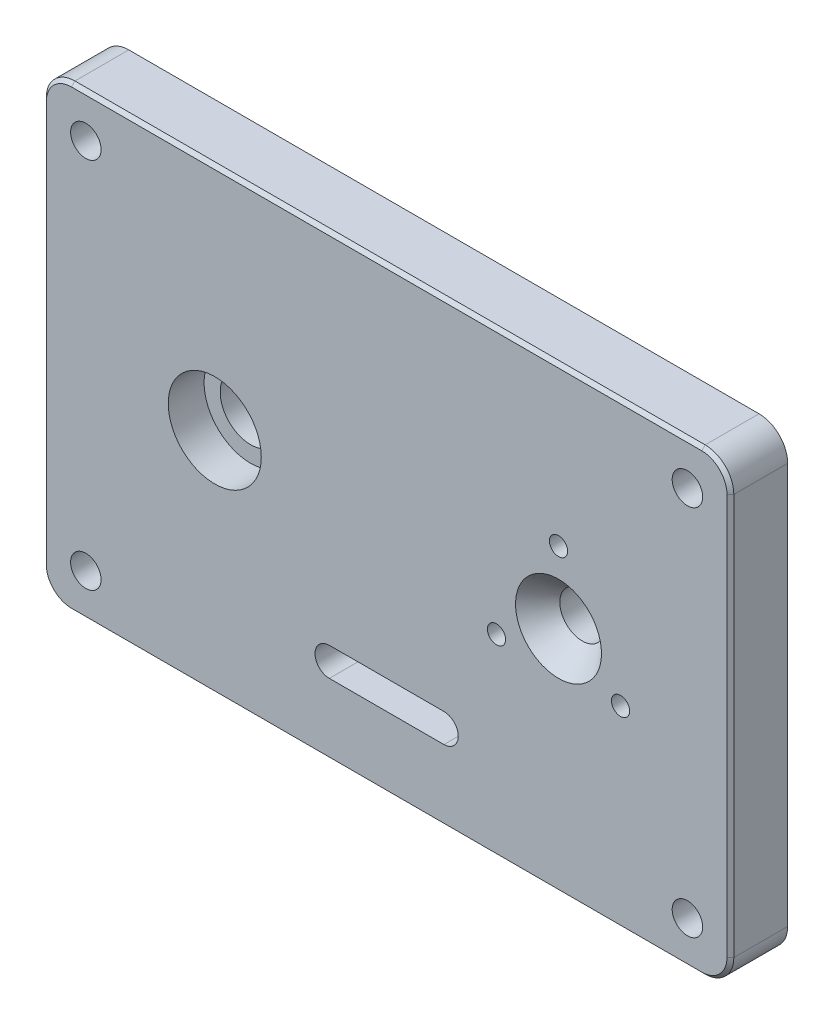
SolidWorks part; units mm, degrees
ref_plane "前视基准面" through (0, 0, 0) normal (0, 0, 1) x (1, 0, 0)
ref_plane "上视基准面" through (0, 0, 0) normal (0, 1, 0) x (1, 0, 0)
ref_plane "右视基准面" through (0, 0, 0) normal (1, 0, 0) x (0, 0, -1)
sketch "草图1" plane through (0, 0, 0) normal (0, 0, 1) x (1, 0, 0)
  line L0 (6.35, 0) -> (146.05, 0)
  line L1 (152.4, 6.35) -> (152.4, 95.25)
  line L2 (146.05, 101.6) -> (6.35, 101.6)
  line L3 (0, 95.25) -> (0, 6.35)
  arc A0 (0, 6.35) -> (6.35, 0) centre (6.35, 6.35) ccw
  arc A1 (146.05, 0) -> (152.4, 6.35) centre (146.05, 6.35) ccw
  arc A2 (152.4, 95.25) -> (146.05, 101.6) centre (146.05, 95.25) ccw
  arc A3 (6.35, 101.6) -> (0, 95.25) centre (6.35, 95.25) ccw
extrude "凸台-拉伸1" add sketch "草图1" along normal blind 12.7
ref_plane "基准面1" through (0, 0, 12.7) normal (0, 0, 1) x (1, 0, 0)
sketch "草图2" plane through (0, 0, 12.7) normal (0, 0, 1) x (1, 0, 0)
  circle A0 centre (9.525, 9.525) radius 3.3782
  circle A1 centre (142.875, 9.525) radius 3.3782
  circle A2 centre (9.525, 92.075) radius 3.3782
  circle A3 centre (142.875, 92.075) radius 3.3782
extrude "切除-拉伸1" cut sketch "草图2" against normal through all
sketch "草图5" plane through (0, 0, 12.7) normal (0, 0, 1) x (1, 0, 0)
  circle A0 centre (38.1, 50.8) radius 10.3125
extrude "切除-拉伸4" cut sketch "草图5" against normal blind 7.95
sketch "草图6" plane through (0, 0, 12.7) normal (0, 0, 1) x (1, 0, 0)
  circle A0 centre (38.1, 50.8) radius 6.7435
extrude "切除-拉伸5" cut sketch "草图6" against normal through all
sketch "草图7" plane through (0, 0, 12.7) normal (0, 0, 1) x (1, 0, 0)
  circle A0 centre (114.3, 50.8) radius 9.525
extrude "切除-拉伸6" cut sketch "草图7" against normal blind 5.2451 draft 41
sketch "草图8" plane through (0, 0, 12.7) normal (0, 0, 1) x (1, 0, 0)
  circle A0 centre (114.3, 50.8) radius 4.9655
extrude "切除-拉伸7" cut sketch "草图8" against normal through all
sketch "草图9" plane through (0, 0, 12.7) normal (0, 0, 1) x (1, 0, 0)
  circle A0 centre (114.3, 66.675) radius 2.0193
  circle A1 centre (100.5518, 42.8625) radius 2.0193
  circle A2 centre (128.0482, 42.8625) radius 2.0193
extrude "切除-拉伸8" cut sketch "草图9" against normal blind 9.525
ref_plane "基准面2" through (0, 0, 3.175) normal (0, 0, 1) x (1, 0, 0)
sketch "草图10" plane through (0, 0, 3.175) normal (0, 0, 1) x (1, 0, 0)
  circle A0 centre (114.3, 66.675) radius 2.0193
  circle A1 centre (100.5518, 42.8625) radius 2.0193
  circle A2 centre (128.0482, 42.8625) radius 2.0193
extrude "切除-拉伸9" cut sketch "草图10" against normal blind 1.2103 draft 59
sketch "草图11" plane through (0, 0, 12.7) normal (0, 0, 1) x (1, 0, 0)
  line L0 (63.5, 15.875) -> (88.9, 15.875)
  line L1 (88.9, 22.225) -> (63.5, 22.225)
  arc A0 (88.9, 15.875) -> (88.9, 22.225) centre (88.9, 19.05) ccw
  arc A1 (63.5, 22.225) -> (63.5, 15.875) centre (63.5, 19.05) ccw
extrude "切除-拉伸10" cut sketch "草图11" against normal through all
chamfer "倒角1" distance 0.762 angle 45 8 edges at (150.5401, 99.7401, 12.7) (76.2, 101.6, 12.7) (1.8599, 99.7401, 12.7) (152.4, 50.8, 12.7) (150.5401, 1.8599, 12.7) (0, 50.8, 12.7) (1.8599, 1.8599, 12.7) (76.2, 0, 12.7)
